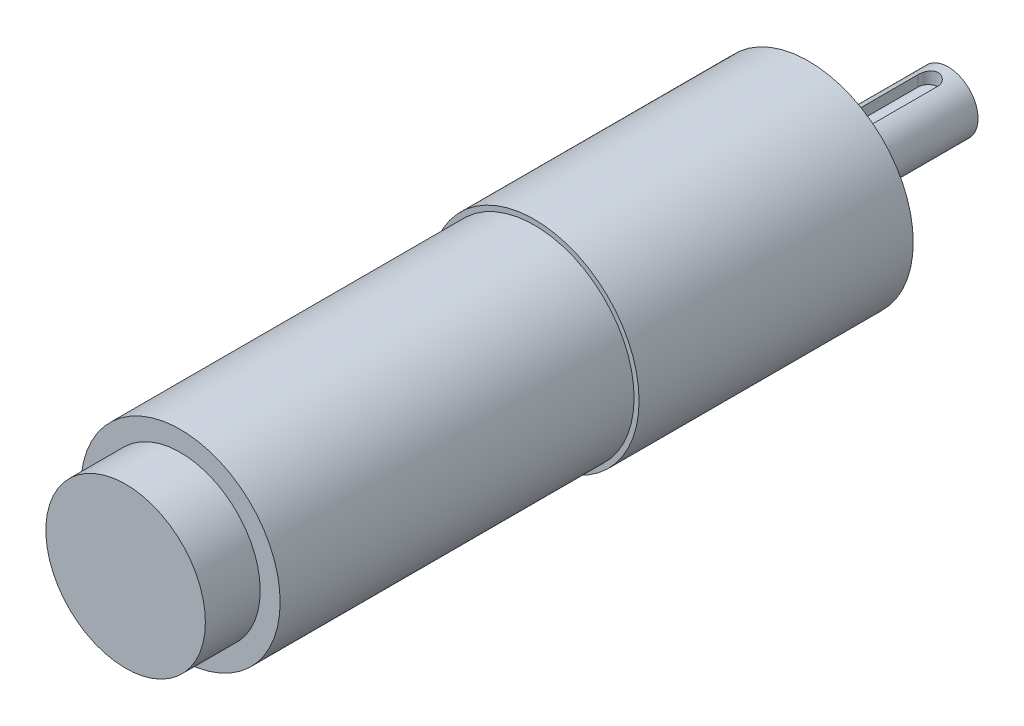
SolidWorks part; units mm, degrees
ref_plane "前视基准面" through (0, 0, 0) normal (0, 0, 1) x (1, 0, 0)
ref_plane "上视基准面" through (0, 0, 0) normal (0, 1, 0) x (1, 0, 0)
ref_plane "右视基准面" through (0, 0, 0) normal (1, 0, 0) x (0, 0, -1)
sketch "草图1" plane through (0, 0, 0) normal (0, 0, 1) x (1, 0, 0)
  circle A0 centre (0, 0) radius 21
  dimension "D1" = 42
extrude "齿轮箱" add sketch "草图1" along normal blind 55
sketch "草图2" plane through (0, 0, 55) normal (0, 0, 1) x (1, 0, 0)
  circle A0 centre (0, 0) radius 20
  dimension "D1" = 40
extrude "电机" add sketch "草图2" along normal blind 71
sketch "草图3" plane through (0, 0, 126) normal (0, 0, 1) x (1, 0, 0)
  line L1 (-15.4942, 0) -> (15.4942, 0) construction
  circle A0 centre (0, 0) radius 16
  dimension "D1" = 32
extrude "编码盘" add sketch "草图3" along normal blind 11
sketch "草图5" plane through (0, 0, 0) normal (0, 0, -1) x (-1, 0, 0)
  circle A0 centre (0, 0) radius 14
  dimension "D1" = 28
extrude "轴承" add sketch "草图5" along normal blind 3
sketch "草图4" plane through (0, 0, -3) normal (0, 0, -1) x (-1, 0, 0)
  circle A0 centre (0, 0) radius 6
  dimension "D1" = 12
extrude "轴" add sketch "草图4" along normal blind 25 separate body
ref_plane "基准面1" through (0, 6, 0) normal (0, 1, 0) x (-1, 0, 0)
sketch "草图6" plane through (0, 6, 0) normal (0, 1, 0) x (-1, 0, 0)
  line L0 (0, 0) -> (0, -29.9259) construction
  line L1 (0, -24) -> (0, -8) construction
  line L2 (-2, -24) -> (-2, -8)
  line L3 (2, -24) -> (2, -8)
  line L4 (-6, -28) -> (6, -28) construction
  arc A0 (-2, -24) -> (2, -24) centre (0, -24) ccw
  arc A1 (2, -8) -> (-2, -8) centre (0, -8) ccw
  point P5 (0, -16)
  dimension "D1" = 4
  dimension "D3" = 16
  dimension "D2" = 4
extrude "切除-拉伸1" cut sketch "草图6" against normal blind 2.5
